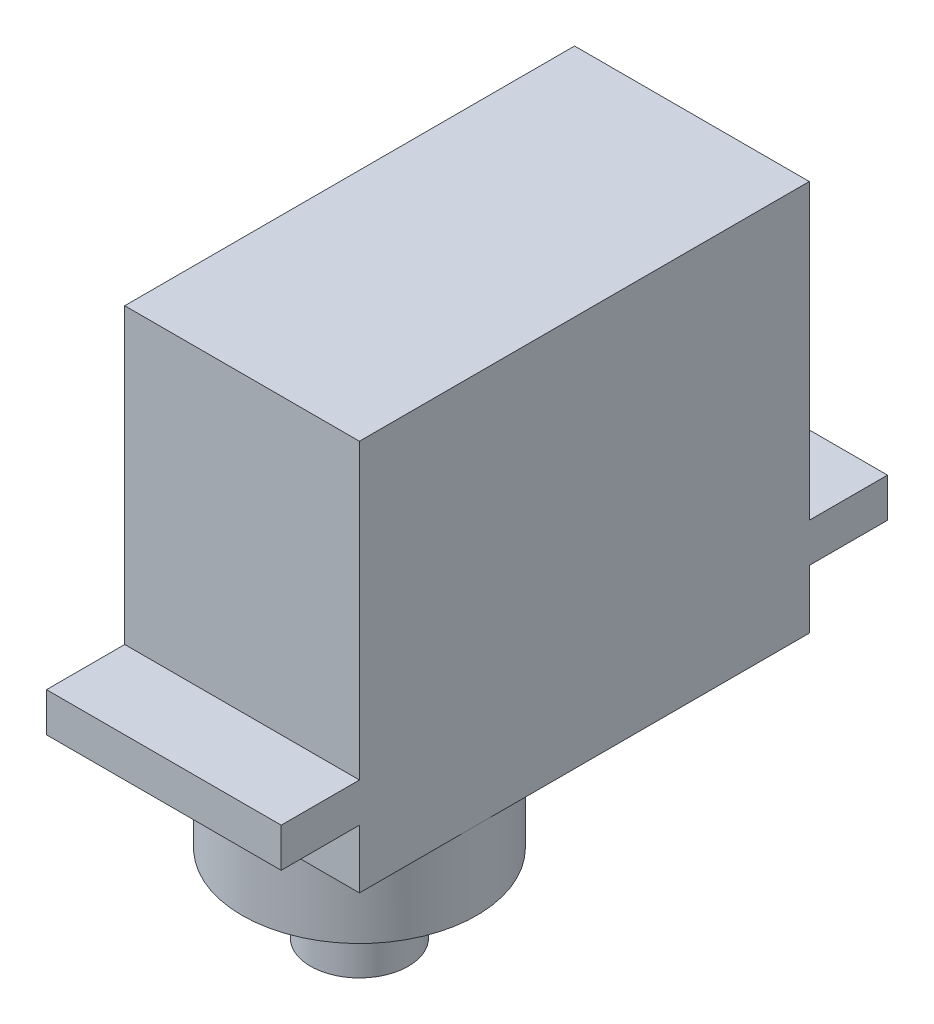
SolidWorks part; units mm, degrees
ref_plane "前视基准面" through (0, 0, 0) normal (0, 0, 1) x (1, 0, 0)
ref_plane "上视基准面" through (0, 0, 0) normal (0, 1, 0) x (1, 0, 0)
ref_plane "右视基准面" through (0, 0, 0) normal (1, 0, 0) x (0, 0, -1)
sketch "草图1" plane through (0, 0, 0) normal (0, 1, 0) x (1, 0, 0)
  line L1 (-6, 11.5) -> (6, 11.5)
  line L2 (-6, 11.5) -> (-6, -11.5)
  line L3 (-6, -11.5) -> (6, -11.5)
  line L4 (6, 11.5) -> (6, -11.5)
  line L5 (-6, 11.5) -> (6, -11.5) construction
  line L6 (-6, -11.5) -> (6, 11.5) construction
  point P0 (0, 0)
  dimension "D1" = 23
  dimension "D2" = 12
extrude "凸台-拉伸2" add sketch "草图1" along normal blind 15 and the other way blind 5
sketch "草图2" plane through (0, -5, 0) normal (0, -1, 0) x (1, 0, 0)
  line L0 (6, 11.5) -> (6, -11.5) construction
  line L1 (-6, -11.5) -> (-6, 11.5) construction
  line L2 (-6, 11.5) -> (6, 11.5) construction
  arc A0 (1.4959, -0.3105) -> (-1.4959, -0.3105) centre (0, 5.5) ccw
  arc A1 (-1.4959, -0.3105) -> (1.4959, -0.3105) centre (0, -0.9927) ccw
extrude "凸台-拉伸3" add sketch "草图2" along normal blind 4
sketch "草图3" plane through (0, -9, 0) normal (0, -1, 0) x (1, 0, 0)
  circle A0 centre (0, 5.5) radius 2.5
  dimension "D1" = 5
extrude "凸台-拉伸4" add sketch "草图3" along normal blind 4
sketch "草图4" plane through (0, 0, 0) normal (0, 1, 0) x (1, 0, 0)
  line L1 (-6, -11.5) -> (6, -11.5)
  line L2 (-6, -11.5) -> (-6, -15.5)
  line L3 (-6, -15.5) -> (6, -15.5)
  line L4 (6, -11.5) -> (6, -15.5)
  dimension "D1" = 12
  dimension "D2" = 4
extrude "凸台-拉伸5" add sketch "草图4" against normal blind 2
mirror "镜向1" about plane through (0, 0, 0) normal (0, 0, 1) of "凸台-拉伸5"
